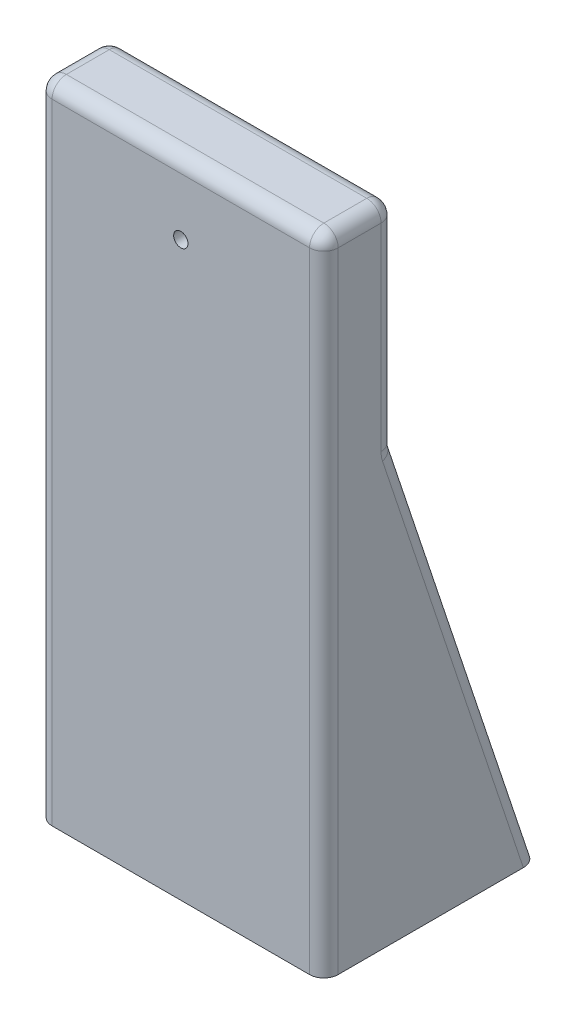
SolidWorks part; units mm, degrees
material "PLA"
ref_plane "Front Plane" through (0, 0, 0) normal (0, 0, 1) x (1, 0, 0)
ref_plane "Top Plane" through (0, 0, 0) normal (0, 1, 0) x (1, 0, 0)
ref_plane "Right Plane" through (0, 0, 0) normal (1, 0, 0) x (0, 0, -1)
sketch "Sketch1" plane through (0, 0, 0) normal (0, 0, 1) x (1, 0, 0)
  line L1 (-25.4, -57.15) -> (25.4, -57.15)
  line L2 (-25.4, -57.15) -> (-25.4, 57.15)
  line L3 (-25.4, 57.15) -> (25.4, 57.15)
  line L4 (25.4, -57.15) -> (25.4, 57.15)
  line L5 (-25.4, -57.15) -> (25.4, 57.15) construction
  line L6 (-25.4, 57.15) -> (25.4, -57.15) construction
  circle A0 centre (0, 44.45) radius 1.27
  point P0 (0, 0)
  dimension "D4" = 2.54
  dimension "D1" = 114.3
  dimension "D2" = 50.8
  dimension "D3" = 101.6
extrude "Boss-Extrude1" add sketch "Sketch1" along normal mid plane 12.7
sketch "Sketch3" plane through (25.4, 0, 0) normal (1, 0, 0) x (0, 0, -1)
  line L0 (6.35, -57.15) -> (31.75, -57.15)
  line L1 (31.75, -57.15) -> (6.35, 19.05)
  line L2 (6.35, -57.15) -> (6.35, 57.15) construction
  line L3 (6.35, 19.05) -> (6.35, -57.15)
  dimension "D1" = 25.4
  dimension "D2" = 76.2
extrude "Boss-Extrude2" add sketch "Sketch3" against normal through all
sketch "Sketch2" plane through (0, -57.15, 0) normal (0, -1, 0) x (1, 0, 0)
  line L0 (-15.24, 0) -> (15.24, 0) construction
  line L2 (-15.24, -22.86) -> (15.24, -22.86) construction
  line L3 (-15.24, -22.86) -> (-15.24, 0) construction
  line L4 (-15.24, 0) -> (15.24, 0) construction
  line L5 (15.24, -22.86) -> (15.24, 0) construction
  line L6 (-15.24, -22.86) -> (15.24, 0) construction
  line L7 (-15.24, 0) -> (15.24, -22.86) construction
  circle A0 centre (-15.24, 0) radius 1.5
  circle A1 centre (15.24, 0) radius 1.5
  circle A2 centre (-15.24, -22.86) radius 1.5
  circle A3 centre (15.24, -22.86) radius 1.5
  point P4 (0, 0)
  point P5 (0, -11.43)
  dimension "D1" = 3
  dimension "D2" = 30.48
  dimension "D3" = 22.86
extrude "Cut-Extrude1" cut sketch "Sketch2" against normal blind 12.7
fillet "Fillet1" radius 2.54 11 edges at (-25.4, -19.05, -19.05) (25.4, -19.05, -19.05) (-25.4, 0, 6.35) (-25.4, 57.15, 0) (25.4, 57.15, 0) (0, 57.15, 6.35) (25.4, 0, 6.35) (-25.4, 38.1, -6.35) (0, 57.15, -6.35) (25.4, 38.1, -6.35) (0, 19.05, -6.35)
